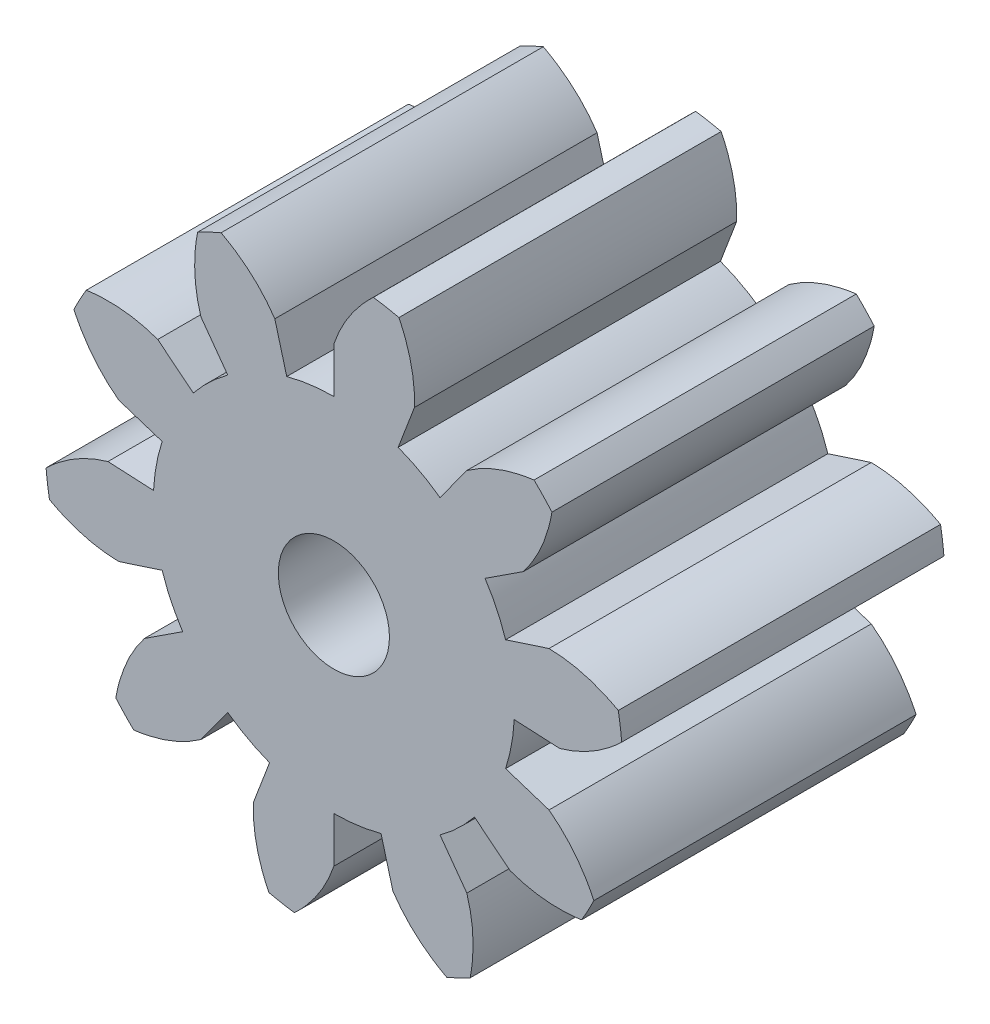
SolidWorks part; units mm, degrees
ref_plane "Front Plane" through (0, 0, 0) normal (0, 0, 1) x (1, 0, 0)
ref_plane "Top Plane" through (0, 0, 0) normal (0, 1, 0) x (1, 0, 0)
ref_plane "Right Plane" through (0, 0, 0) normal (1, 0, 0) x (0, 0, -1)
sketch "Sketch1" plane through (0, 0, 0) normal (0, 0, 1) x (1, 0, 0)
  line L0 (0, 30.535) -> (19.2447, 23.7072) construction
  line L1 (19.2447, 23.7072) -> (29.8828, 6.2771) construction
  line L2 (29.8828, 6.2771) -> (27.157, -13.9601) construction
  line L3 (27.157, -13.9601) -> (12.2861, -27.9542) construction
  line L4 (19.2447, 23.7072) -> (3.3907, 36.5768) construction
  line L5 (29.8828, 6.2771) -> (21.4873, 46.2449) construction
  line L6 (27.157, -13.9601) -> (55.1641, 40.5228) construction
  line L7 (12.2861, -27.9542) -> (87.0626, 4.9108) construction
  line L8 (0.7914, 32.4904) -> (10.8326, 30.6416) construction
  line L9 (5.812, 31.566) -> (0, 0) construction
  line L10 (0, 30.535) -> (0, 0)
  line L11 (0, 0) -> (10.8756, 28.5326)
  circle A0 centre (0, 0) radius 39
  circle A1 centre (0, 0) radius 32.5 construction
  circle A2 centre (0, 0) radius 30.535 construction
  circle A3 centre (0, 0) radius 24.375
  spline S0 degree 3 poles (0, 30.535) (3.0693, 39.5236) (39.5395, 59.0602) (77.9422, 29.6488) (87.0626, 4.9108) knots 0 0 0 0 0.25084 1 1 1 1
  spline S1 degree 3 poles (10.8756, 28.5326) (11.209, 38.0249) (-15.9111, 69.2699) (-62.2709, 55.4651) (-79.6041, 35.5977) knots 0 0 0 0 0.25084 1 1 1 1
  dimension "D1" = 78
  dimension "D2" = 65
  dimension "D3" = 61.07
  dimension "D4" = 48.75
  dimension "D5" = 20.42
  dimension "D6" = 20.42
  dimension "D7" = 40.84
  dimension "D8" = 61.26
  dimension "D9" = 81.68
  dimension "D10" = 10.21
extrude "Boss-Extrude1" add sketch "Sketch1" along normal blind 43.5 contours L10 A3 L11 | L11 A3 L10 | L11 S1 A0 S0 L10 A3
pattern_circular "CirPattern1" count 10 over 360 about axis through (0, 0, 43.5) along (0, 0, 1) of "Boss-Extrude1"
sketch "Sketch2" plane through (0, 0, 43.5) normal (0, 0, 1) x (1, 0, 0)
  circle A0 centre (0, 0) radius 7.5
  dimension "D1" = 15
extrude "Cut-Extrude1" cut sketch "Sketch2" against normal through all
